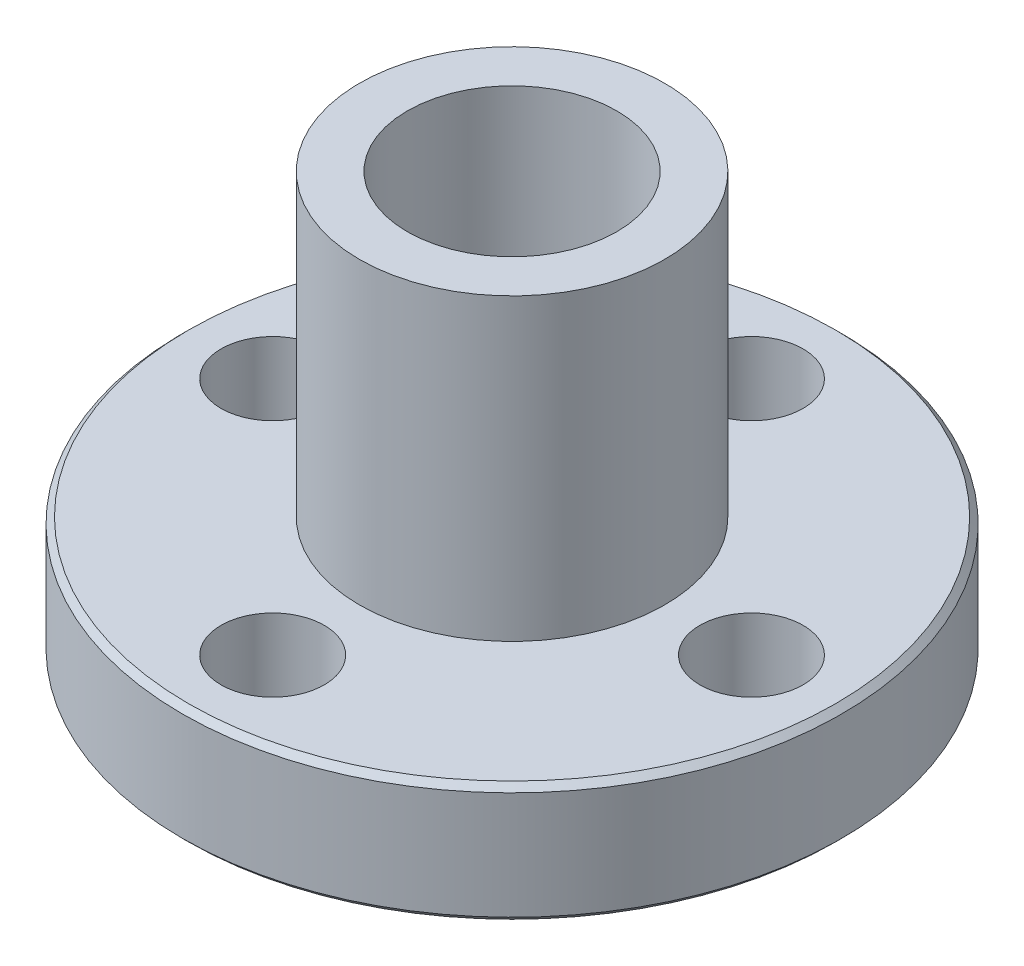
SolidWorks part; units mm, degrees
ref_plane "Front Plane" through (0, 0, 0) normal (0, 0, 1) x (1, 0, 0)
ref_plane "Top Plane" through (0, 0, 0) normal (0, 1, 0) x (1, 0, 0)
ref_plane "Right Plane" through (0, 0, 0) normal (1, 0, 0) x (0, 0, -1)
sketch "Sketch1" plane through (0, 0, 0) normal (0, 1, 0) x (1, 0, 0)
  circle A0 centre (0, 0) radius 11.013
  circle A1 centre (0, 0) radius 3.5
  dimension "D1" = 7
extrude "Boss-Extrude1" add sketch "Sketch1" along normal blind 4
sketch "Sketch2" plane through (0, 4, 0) normal (0, 1, 0) x (1, 0, 0)
  line L0 (0, 0) -> (8, 0) construction
  circle A0 centre (8, 0) radius 1.725
  circle A1 centre (0, -8) radius 1.725
  circle A2 centre (-8, 0) radius 1.725
  circle A3 centre (0, 8) radius 1.725
  circle A4 centre (0, 0) radius 11.013 construction
  point P13 (0, 0)
  dimension "D1" = 3.45
  dimension "D4" = 8
  dimension "D2" = 4
sketch "Sketch3" plane through (0, 4, 0) normal (0, 1, 0) x (1, 0, 0)
  circle A0 centre (0, 0) radius 5.1
  circle A1 centre (0, 0) radius 3.5
  dimension "D1" = 10.2
extrude "Boss-Extrude2" add sketch "Sketch3" along normal blind 10
sketch "Sketch4" plane through (0, 0, 0) normal (0, -1, 0) x (-1, 0, 0)
  circle A0 centre (0, 0) radius 3.5
  circle A1 centre (0, 0) radius 5.125
  dimension "D1" = 10.25
extrude "Boss-Extrude3" add sketch "Sketch4" along normal blind 1.25
chamfer "Chamfer1" distance 0.2 angle 45 2 edges at (0, 0, 11.013) (0, 4, 11.013)
extrude "Cut-Extrude1" cut sketch "Sketch2" against normal blind 10
